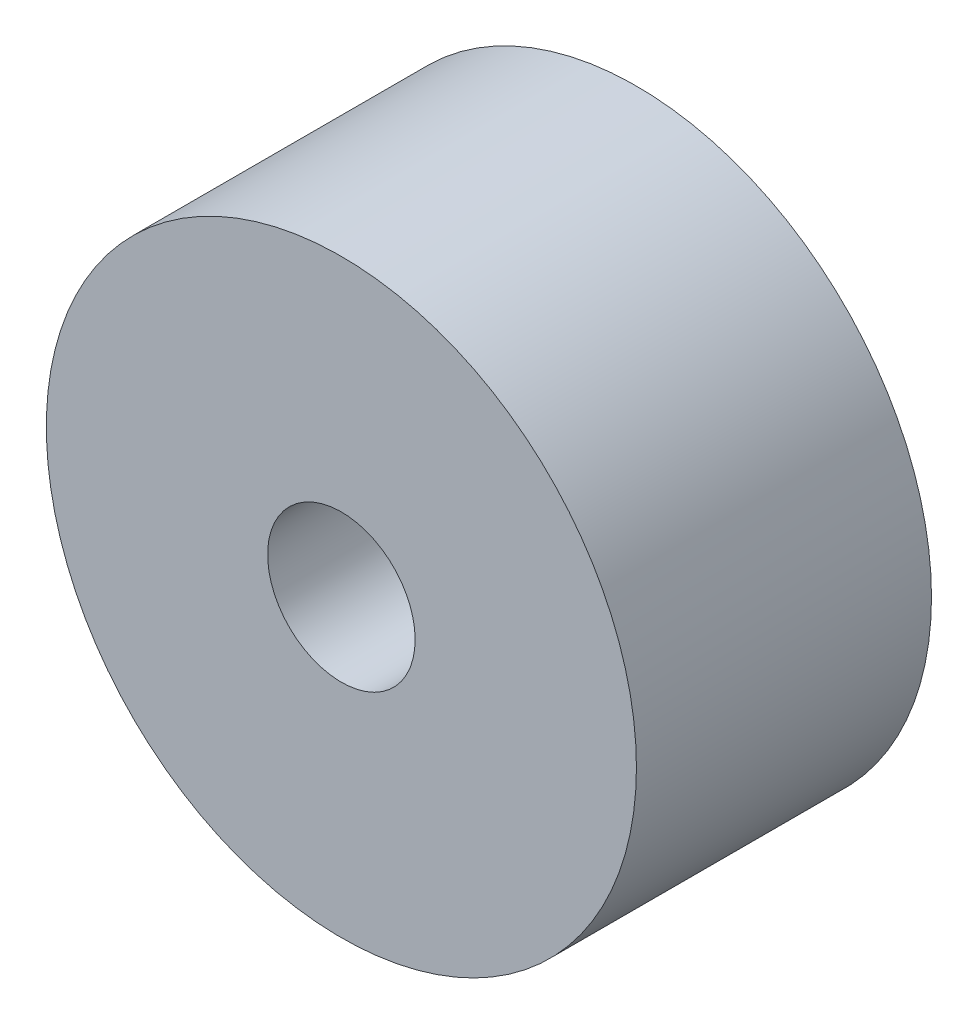
SolidWorks part; units mm, degrees
ref_plane "Piano frontale" through (0, 0, 0) normal (0, 0, 1) x (1, 0, 0)
ref_plane "Piano superiore" through (0, 0, 0) normal (0, 1, 0) x (1, 0, 0)
ref_plane "Piano destro" through (0, 0, 0) normal (1, 0, 0) x (0, 0, -1)
sketch "Schizzo1" plane through (0, 0, 0) normal (0, 0, 1) x (1, 0, 0)
  circle A0 centre (0, 0) radius 2.5
  circle A1 centre (0, 0) radius 10
  dimension "D1" = 20
  dimension "D2" = 5
extrude "Estrusione-Estrusione1" add sketch "Schizzo1" along normal blind 10
